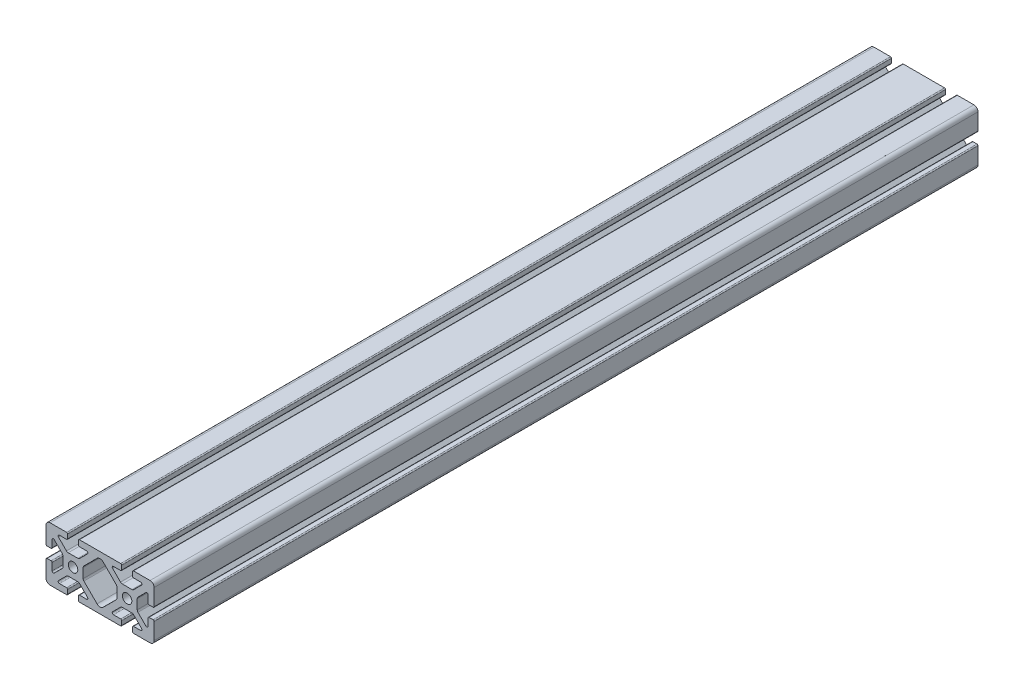
SolidWorks part; units mm, degrees
ref_plane "Front Plane" through (0, 0, 0) normal (0, 0, 1) x (1, 0, 0)
ref_plane "Top Plane" through (0, 0, 0) normal (0, 1, 0) x (1, 0, 0)
ref_plane "Right Plane" through (0, 0, 0) normal (1, 0, 0) x (0, 0, -1)
sketch "Sketch1" plane through (0, 0, 0) normal (0, 0, 1) x (1, 0, 0)
  line L0 (-40, 17) -> (-40, 4.75)
  line L1 (-37, 20) -> (-24.75, 20)
  line L2 (-24, 19.25) -> (-24, 16.25)
  line L3 (-24.75, 15.5) -> (-30.068, 15.5)
  line L4 (-30.727, 13.909) -> (-24.8599, 8.0419)
  line L5 (-33.909, 10.727) -> (-28.0419, 4.8599)
  line L6 (-35.5, 10.068) -> (-35.5, 4.75)
  line L7 (-36.25, 4) -> (-39.25, 4)
  line L8 (-23.5517, 7.5) -> (-16.4483, 7.5)
  line L9 (-27.5, 3.5517) -> (-27.5, -3.5517)
  line L10 (0, 20) -> (-15.25, 20)
  line L11 (-16, 19.25) -> (-16, 16.25)
  line L12 (-15.25, 15.5) -> (-9.932, 15.5)
  line L13 (-12.5, 3.5517) -> (-12.5, -3.5517)
  line L14 (-9.273, 13.909) -> (-15.1401, 8.0419)
  line L15 (-2.25, 14.568) -> (-11.9581, 4.8599)
  line L16 (-36.25, -4) -> (-39.25, -4)
  line L17 (-35.5, -10.068) -> (-35.5, -4.75)
  line L18 (-33.909, -10.727) -> (-28.0419, -4.8599)
  line L19 (-30.727, -13.909) -> (-24.8599, -8.0419)
  line L20 (-24.75, -15.5) -> (-30.068, -15.5)
  line L21 (-24, -19.25) -> (-24, -16.25)
  line L22 (-37, -20) -> (-24.75, -20)
  line L23 (-40, -17) -> (-40, -4.75)
  line L24 (0, -20) -> (-15.25, -20)
  line L25 (-16, -19.25) -> (-16, -16.25)
  line L26 (-15.25, -15.5) -> (-9.932, -15.5)
  line L27 (-9.273, -13.909) -> (-15.1401, -8.0419)
  line L28 (-2.25, -14.568) -> (-11.9581, -4.8599)
  line L29 (-23.5517, -7.5) -> (-16.4483, -7.5)
  line L58 (0, 20) -> (0, -20) construction
  line L59 (-12.5, 0) -> (0, 0) construction
  line L60 (0, 15.5) -> (15.25, 15.5) construction
  line L61 (0, -15.5) -> (15.25, -15.5) construction
  line L62 (-24, 17.75) -> (-16, 17.75) construction
  line L63 (-20, 17.75) -> (-20, 0) construction
  line L64 (-37.75, 4) -> (-37.75, -4) construction
  circle A0 centre (-20, 0) radius 3.5
  arc A1 (-40, 17) -> (-37, 20) centre (-37, 17) cw
  arc A2 (-33.909, 10.727) -> (-35.5, 10.068) centre (-34.568, 10.068) ccw
  arc A3 (-30.068, 15.5) -> (-30.727, 13.909) centre (-30.068, 14.568) ccw
  arc A4 (-24.75, 20) -> (-24, 19.25) centre (-24.75, 19.25) cw
  arc A5 (-40, 4.75) -> (-39.25, 4) centre (-39.25, 4.75) ccw
  arc A6 (-35.5, 4.75) -> (-36.25, 4) centre (-36.25, 4.75) cw
  arc A7 (-24, 16.25) -> (-24.75, 15.5) centre (-24.75, 16.25) cw
  arc A8 (-23.5517, 7.5) -> (-24.8599, 8.0419) centre (-23.5517, 9.35) cw
  arc A9 (-27.5, 3.5517) -> (-28.0419, 4.8599) centre (-29.35, 3.5517) ccw
  arc A10 (0, 15.5) -> (-2.25, 14.568) centre (0, 12.318) ccw
  arc A11 (-2.25, -14.568) -> (0, -15.5) centre (0, -12.318) ccw
  arc A12 (-15.25, 20) -> (-16, 19.25) centre (-15.25, 19.25) ccw
  arc A13 (-16, 16.25) -> (-15.25, 15.5) centre (-15.25, 16.25) ccw
  arc A14 (-16.4483, 7.5) -> (-15.1401, 8.0419) centre (-16.4483, 9.35) ccw
  arc A15 (-12.5, 3.5517) -> (-11.9581, 4.8599) centre (-10.65, 3.5517) cw
  arc A16 (-9.932, 15.5) -> (-9.273, 13.909) centre (-9.932, 14.568) cw
  arc A17 (-27.5, -3.5517) -> (-28.0419, -4.8599) centre (-29.35, -3.5517) cw
  arc A18 (-23.5517, -7.5) -> (-24.8599, -8.0419) centre (-23.5517, -9.35) ccw
  arc A19 (-24, -16.25) -> (-24.75, -15.5) centre (-24.75, -16.25) ccw
  arc A20 (-35.5, -4.75) -> (-36.25, -4) centre (-36.25, -4.75) ccw
  arc A21 (-40, -4.75) -> (-39.25, -4) centre (-39.25, -4.75) cw
  arc A22 (-24.75, -20) -> (-24, -19.25) centre (-24.75, -19.25) ccw
  arc A23 (-30.068, -15.5) -> (-30.727, -13.909) centre (-30.068, -14.568) cw
  arc A24 (-33.909, -10.727) -> (-35.5, -10.068) centre (-34.568, -10.068) cw
  arc A25 (-40, -17) -> (-37, -20) centre (-37, -17) ccw
  arc A26 (-9.932, -15.5) -> (-9.273, -13.909) centre (-9.932, -14.568) ccw
  arc A27 (-15.25, -20) -> (-16, -19.25) centre (-15.25, -19.25) cw
  arc A28 (-16, -16.25) -> (-15.25, -15.5) centre (-15.25, -16.25) cw
  arc A29 (-16.4483, -7.5) -> (-15.1401, -8.0419) centre (-16.4483, -9.35) cw
  arc A30 (-12.5, -3.5517) -> (-11.9581, -4.8599) centre (-10.65, -3.5517) ccw
  point P36 (-27.5, 0)
  point P98 (-37.75, 0)
  point P103 (-20, 7.5)
  point P105 (-20, -7.5)
  dimension "D7" = 7
  dimension "D9" = 3
  dimension "D17" = 0.75
  dimension "D23" = 1.85
  dimension "Rail Width" = 40
  dimension "Rail Height" = 80
  dimension "D3" = 40
  dimension "D4" = 20
  dimension "D6" = 4.5
  dimension "D8" = 4.5
  dimension "D10" = 4.5
  dimension "D11" = 4.5
  dimension "Slot Width" = 8
  dimension "D13" = 45
  dimension "D14" = 45
  dimension "D15" = 4.5
  dimension "D16" = 8
  dimension "D19" = 8
  dimension "D20" = 7.5
  dimension "D21" = 8
  dimension "D22" = 7.5
  dimension "D5" = 22
  dimension "D18" = 22
sketch "Sketch2" plane through (0, 0, 0) normal (1, 0, 0) x (0, 0, -1)
  line L0 (-304.8, -20) -> (304.8, -20)
  point P2 (-266.7, -20)
  point P3 (266.7, -20)
  dimension "Length" = 609.6
  dimension "D1" = 38.1
  dimension "D2" = 38.1
sketch "Sketch3" plane through (0, 0, 0) normal (0, 0, 1) x (1, 0, 0)
  line L0 (0, 20) -> (-15.25, 20) construction
  line L1 (-16, 19.25) -> (-16, 16.25) construction
  line L2 (-15.25, 15.5) -> (-9.932, 15.5) construction
  line L3 (-9.273, 13.909) -> (-15.1401, 8.0419) construction
  line L4 (-23.5517, 7.5) -> (-16.4483, 7.5) construction
  line L5 (-30.727, 13.909) -> (-24.8599, 8.0419) construction
  line L6 (-24.75, 15.5) -> (-30.068, 15.5) construction
  line L7 (-24, 19.25) -> (-24, 16.25) construction
  line L8 (-37, 20) -> (-24.75, 20) construction
  line L9 (-40, 17) -> (-40, 4.75) construction
  line L10 (-36.25, 4) -> (-39.25, 4) construction
  line L11 (-35.5, 10.068) -> (-35.5, 4.75) construction
  line L12 (-33.909, 10.727) -> (-28.0419, 4.8599) construction
  line L13 (-27.5, 3.5517) -> (-27.5, -3.5517) construction
  line L14 (-33.909, -10.727) -> (-28.0419, -4.8599) construction
  line L15 (-35.5, -10.068) -> (-35.5, -4.75) construction
  line L16 (-36.25, -4) -> (-39.25, -4) construction
  line L17 (-40, -17) -> (-40, -4.75) construction
  line L18 (-37, -20) -> (-24.75, -20) construction
  line L19 (-24, -19.25) -> (-24, -16.25) construction
  line L20 (-24.75, -15.5) -> (-30.068, -15.5) construction
  line L21 (-30.727, -13.909) -> (-24.8599, -8.0419) construction
  line L22 (-23.5517, -7.5) -> (-16.4483, -7.5) construction
  line L23 (-9.273, -13.909) -> (-15.1401, -8.0419) construction
  line L24 (-15.25, -15.5) -> (-9.932, -15.5) construction
  line L25 (-16, -19.25) -> (-16, -16.25) construction
  line L26 (0, -20) -> (-15.25, -20) construction
  line L27 (-2.25, -14.568) -> (-11.9581, -4.8599) construction
  line L28 (-12.5, 3.5517) -> (-12.5, -3.5517) construction
  line L29 (-2.25, 14.568) -> (-11.9581, 4.8599) construction
  line L30 (15.25, 20) -> (-15.25, 20)
  line L31 (-16, 19.25) -> (-16, 16.25)
  line L32 (-15.25, 15.5) -> (-9.932, 15.5)
  line L33 (-9.273, 13.909) -> (-15.1401, 8.0419)
  line L34 (-23.5517, 7.5) -> (-16.4483, 7.5)
  line L35 (-30.727, 13.909) -> (-24.8599, 8.0419)
  line L36 (-24.75, 15.5) -> (-30.068, 15.5)
  line L37 (-24, 19.25) -> (-24, 16.25)
  line L38 (-37, 20) -> (-24.75, 20)
  line L39 (-40, 17) -> (-40, 4.75)
  line L40 (-36.25, 4) -> (-39.25, 4)
  line L41 (-35.5, 10.068) -> (-35.5, 4.75)
  line L42 (-33.909, 10.727) -> (-28.0419, 4.8599)
  line L43 (-27.5, 3.5517) -> (-27.5, -3.5517)
  line L44 (-33.909, -10.727) -> (-28.0419, -4.8599)
  line L45 (-35.5, -10.068) -> (-35.5, -4.75)
  line L46 (-36.25, -4) -> (-39.25, -4)
  line L47 (-40, -17) -> (-40, -4.75)
  line L48 (-37, -20) -> (-24.75, -20)
  line L49 (-24, -19.25) -> (-24, -16.25)
  line L50 (-24.75, -15.5) -> (-30.068, -15.5)
  line L51 (-30.727, -13.909) -> (-24.8599, -8.0419)
  line L52 (-23.5517, -7.5) -> (-16.4483, -7.5)
  line L53 (-9.273, -13.909) -> (-15.1401, -8.0419)
  line L54 (-15.25, -15.5) -> (-9.932, -15.5)
  line L55 (-16, -19.25) -> (-16, -16.25)
  line L56 (15.25, -20) -> (-15.25, -20)
  line L57 (-2.25, -14.568) -> (-11.9581, -4.8599)
  line L58 (-12.5, 3.5517) -> (-12.5, -3.5517)
  line L59 (-2.25, 14.568) -> (-11.9581, 4.8599)
  line L60 (0, 20) -> (0, -20) construction
  line L61 (2.25, 14.568) -> (11.9581, 4.8599)
  line L62 (12.5, 3.5517) -> (12.5, -3.5517)
  line L63 (2.25, -14.568) -> (11.9581, -4.8599)
  line L64 (16, 19.25) -> (16, 16.25)
  line L65 (15.25, 15.5) -> (9.932, 15.5)
  line L66 (9.273, 13.909) -> (15.1401, 8.0419)
  line L67 (23.5517, 7.5) -> (16.4483, 7.5)
  line L68 (30.727, 13.909) -> (24.8599, 8.0419)
  line L69 (24.75, 15.5) -> (30.068, 15.5)
  line L70 (24, 19.25) -> (24, 16.25)
  line L71 (37, 20) -> (24.75, 20)
  line L72 (40, 17) -> (40, 4.75)
  line L73 (36.25, 4) -> (39.25, 4)
  line L74 (35.5, 10.068) -> (35.5, 4.75)
  line L75 (33.909, 10.727) -> (28.0419, 4.8599)
  line L76 (27.5, 3.5517) -> (27.5, -3.5517)
  line L77 (33.909, -10.727) -> (28.0419, -4.8599)
  line L78 (35.5, -10.068) -> (35.5, -4.75)
  line L79 (36.25, -4) -> (39.25, -4)
  line L80 (40, -17) -> (40, -4.75)
  line L81 (37, -20) -> (24.75, -20)
  line L82 (24, -19.25) -> (24, -16.25)
  line L83 (24.75, -15.5) -> (30.068, -15.5)
  line L84 (30.727, -13.909) -> (24.8599, -8.0419)
  line L85 (23.5517, -7.5) -> (16.4483, -7.5)
  line L86 (9.273, -13.909) -> (15.1401, -8.0419)
  line L87 (15.25, -15.5) -> (9.932, -15.5)
  line L88 (16, -19.25) -> (16, -16.25)
  circle A0 centre (-20, 0) radius 3.5 construction
  arc A1 (-15.25, 20) -> (-16, 19.25) centre (-15.25, 19.25) ccw construction
  arc A2 (-16, 16.25) -> (-15.25, 15.5) centre (-15.25, 16.25) ccw construction
  arc A3 (-9.273, 13.909) -> (-9.932, 15.5) centre (-9.932, 14.568) ccw construction
  arc A4 (-16.4483, 7.5) -> (-15.1401, 8.0419) centre (-16.4483, 9.35) ccw construction
  arc A5 (-24.8599, 8.0419) -> (-23.5517, 7.5) centre (-23.5517, 9.35) ccw construction
  arc A6 (-30.068, 15.5) -> (-30.727, 13.909) centre (-30.068, 14.568) ccw construction
  arc A7 (-24.75, 15.5) -> (-24, 16.25) centre (-24.75, 16.25) ccw construction
  arc A8 (-24, 19.25) -> (-24.75, 20) centre (-24.75, 19.25) ccw construction
  arc A9 (-37, 20) -> (-40, 17) centre (-37, 17) ccw construction
  arc A10 (-40, 4.75) -> (-39.25, 4) centre (-39.25, 4.75) ccw construction
  arc A11 (-36.25, 4) -> (-35.5, 4.75) centre (-36.25, 4.75) ccw construction
  arc A12 (-33.909, 10.727) -> (-35.5, 10.068) centre (-34.568, 10.068) ccw construction
  arc A13 (-27.5, 3.5517) -> (-28.0419, 4.8599) centre (-29.35, 3.5517) ccw construction
  arc A14 (-28.0419, -4.8599) -> (-27.5, -3.5517) centre (-29.35, -3.5517) ccw construction
  arc A15 (-35.5, -10.068) -> (-33.909, -10.727) centre (-34.568, -10.068) ccw construction
  arc A16 (-35.5, -4.75) -> (-36.25, -4) centre (-36.25, -4.75) ccw construction
  arc A17 (-39.25, -4) -> (-40, -4.75) centre (-39.25, -4.75) ccw construction
  arc A18 (-40, -17) -> (-37, -20) centre (-37, -17) ccw construction
  arc A19 (-24.75, -20) -> (-24, -19.25) centre (-24.75, -19.25) ccw construction
  arc A20 (-24, -16.25) -> (-24.75, -15.5) centre (-24.75, -16.25) ccw construction
  arc A21 (-30.727, -13.909) -> (-30.068, -15.5) centre (-30.068, -14.568) ccw construction
  arc A22 (-23.5517, -7.5) -> (-24.8599, -8.0419) centre (-23.5517, -9.35) ccw construction
  arc A23 (-15.1401, -8.0419) -> (-16.4483, -7.5) centre (-16.4483, -9.35) ccw construction
  arc A24 (-9.932, -15.5) -> (-9.273, -13.909) centre (-9.932, -14.568) ccw construction
  arc A25 (-15.25, -15.5) -> (-16, -16.25) centre (-15.25, -16.25) ccw construction
  arc A26 (-16, -19.25) -> (-15.25, -20) centre (-15.25, -19.25) ccw construction
  arc A27 (-2.25, -14.568) -> (0, -15.5) centre (0, -12.318) ccw construction
  arc A28 (-12.5, -3.5517) -> (-11.9581, -4.8599) centre (-10.65, -3.5517) ccw construction
  arc A29 (-11.9581, 4.8599) -> (-12.5, 3.5517) centre (-10.65, 3.5517) ccw construction
  arc A30 (0, 15.5) -> (-2.25, 14.568) centre (0, 12.318) ccw construction
  circle A31 centre (-20, 0) radius 3.5
  arc A32 (-15.25, 20) -> (-16, 19.25) centre (-15.25, 19.25) ccw
  arc A33 (-16, 16.25) -> (-15.25, 15.5) centre (-15.25, 16.25) ccw
  arc A34 (-9.273, 13.909) -> (-9.932, 15.5) centre (-9.932, 14.568) ccw
  arc A35 (-16.4483, 7.5) -> (-15.1401, 8.0419) centre (-16.4483, 9.35) ccw
  arc A36 (-24.8599, 8.0419) -> (-23.5517, 7.5) centre (-23.5517, 9.35) ccw
  arc A37 (-30.068, 15.5) -> (-30.727, 13.909) centre (-30.068, 14.568) ccw
  arc A38 (-24.75, 15.5) -> (-24, 16.25) centre (-24.75, 16.25) ccw
  arc A39 (-24, 19.25) -> (-24.75, 20) centre (-24.75, 19.25) ccw
  arc A40 (-37, 20) -> (-40, 17) centre (-37, 17) ccw
  arc A41 (-40, 4.75) -> (-39.25, 4) centre (-39.25, 4.75) ccw
  arc A42 (-36.25, 4) -> (-35.5, 4.75) centre (-36.25, 4.75) ccw
  arc A43 (-33.909, 10.727) -> (-35.5, 10.068) centre (-34.568, 10.068) ccw
  arc A44 (-27.5, 3.5517) -> (-28.0419, 4.8599) centre (-29.35, 3.5517) ccw
  arc A45 (-28.0419, -4.8599) -> (-27.5, -3.5517) centre (-29.35, -3.5517) ccw
  arc A46 (-35.5, -10.068) -> (-33.909, -10.727) centre (-34.568, -10.068) ccw
  arc A47 (-35.5, -4.75) -> (-36.25, -4) centre (-36.25, -4.75) ccw
  arc A48 (-39.25, -4) -> (-40, -4.75) centre (-39.25, -4.75) ccw
  arc A49 (-40, -17) -> (-37, -20) centre (-37, -17) ccw
  arc A50 (-24.75, -20) -> (-24, -19.25) centre (-24.75, -19.25) ccw
  arc A51 (-24, -16.25) -> (-24.75, -15.5) centre (-24.75, -16.25) ccw
  arc A52 (-30.727, -13.909) -> (-30.068, -15.5) centre (-30.068, -14.568) ccw
  arc A53 (-23.5517, -7.5) -> (-24.8599, -8.0419) centre (-23.5517, -9.35) ccw
  arc A54 (-15.1401, -8.0419) -> (-16.4483, -7.5) centre (-16.4483, -9.35) ccw
  arc A55 (-9.932, -15.5) -> (-9.273, -13.909) centre (-9.932, -14.568) ccw
  arc A56 (-15.25, -15.5) -> (-16, -16.25) centre (-15.25, -16.25) ccw
  arc A57 (-16, -19.25) -> (-15.25, -20) centre (-15.25, -19.25) ccw
  arc A58 (-2.25, -14.568) -> (2.25, -14.568) centre (0, -12.318) ccw
  arc A59 (-12.5, -3.5517) -> (-11.9581, -4.8599) centre (-10.65, -3.5517) ccw
  arc A60 (-11.9581, 4.8599) -> (-12.5, 3.5517) centre (-10.65, 3.5517) ccw
  arc A61 (2.25, 14.568) -> (-2.25, 14.568) centre (0, 12.318) ccw
  circle A62 centre (20, 0) radius 3.5
  arc A63 (11.9581, 4.8599) -> (12.5, 3.5517) centre (10.65, 3.5517) cw
  arc A64 (12.5, -3.5517) -> (11.9581, -4.8599) centre (10.65, -3.5517) cw
  arc A65 (15.25, 20) -> (16, 19.25) centre (15.25, 19.25) cw
  arc A66 (16, 16.25) -> (15.25, 15.5) centre (15.25, 16.25) cw
  arc A67 (9.273, 13.909) -> (9.932, 15.5) centre (9.932, 14.568) cw
  arc A68 (16.4483, 7.5) -> (15.1401, 8.0419) centre (16.4483, 9.35) cw
  arc A69 (24.8599, 8.0419) -> (23.5517, 7.5) centre (23.5517, 9.35) cw
  arc A70 (30.068, 15.5) -> (30.727, 13.909) centre (30.068, 14.568) cw
  arc A71 (24.75, 15.5) -> (24, 16.25) centre (24.75, 16.25) cw
  arc A72 (24, 19.25) -> (24.75, 20) centre (24.75, 19.25) cw
  arc A73 (37, 20) -> (40, 17) centre (37, 17) cw
  arc A74 (40, 4.75) -> (39.25, 4) centre (39.25, 4.75) cw
  arc A75 (36.25, 4) -> (35.5, 4.75) centre (36.25, 4.75) cw
  arc A76 (33.909, 10.727) -> (35.5, 10.068) centre (34.568, 10.068) cw
  arc A77 (27.5, 3.5517) -> (28.0419, 4.8599) centre (29.35, 3.5517) cw
  arc A78 (28.0419, -4.8599) -> (27.5, -3.5517) centre (29.35, -3.5517) cw
  arc A79 (35.5, -10.068) -> (33.909, -10.727) centre (34.568, -10.068) cw
  arc A80 (35.5, -4.75) -> (36.25, -4) centre (36.25, -4.75) cw
  arc A81 (39.25, -4) -> (40, -4.75) centre (39.25, -4.75) cw
  arc A82 (40, -17) -> (37, -20) centre (37, -17) cw
  arc A83 (24.75, -20) -> (24, -19.25) centre (24.75, -19.25) cw
  arc A84 (24, -16.25) -> (24.75, -15.5) centre (24.75, -16.25) cw
  arc A85 (30.727, -13.909) -> (30.068, -15.5) centre (30.068, -14.568) cw
  arc A86 (23.5517, -7.5) -> (24.8599, -8.0419) centre (23.5517, -9.35) cw
  arc A87 (15.1401, -8.0419) -> (16.4483, -7.5) centre (16.4483, -9.35) cw
  arc A88 (9.932, -15.5) -> (9.273, -13.909) centre (9.932, -14.568) cw
  arc A89 (15.25, -15.5) -> (16, -16.25) centre (15.25, -16.25) cw
  arc A90 (16, -19.25) -> (15.25, -20) centre (15.25, -19.25) cw
extrude "Boss-Extrude1" add sketch "Sketch3" along normal mid plane 609.6
equation "\"D10@Sketch1\"=\"D8@Sketch1\""
equation "\"D11@Sketch1\"=\"D10@Sketch1\""
equation "\"D15@Sketch1\"=\"D6@Sketch1\""
equation "\"D16@Sketch1\" = \"Slot Width@Sketch1\""
equation "\"D18@Sketch1\"=\"D5@Sketch1\""
equation "\"D1@Boss-Extrude1\"=\"Length@Sketch2\""
equation "\"D2@Sketch2\"=\"D1@Sketch2\""
